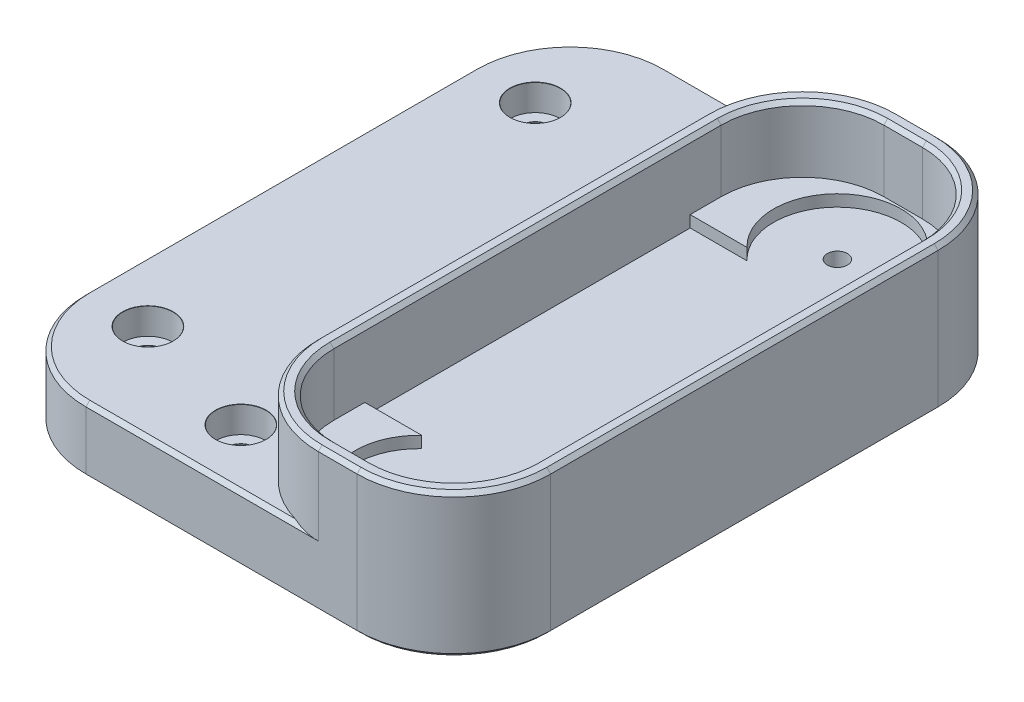
SolidWorks part; units mm, degrees
material "ABS"
ref_plane "Front Plane" through (0, 0, 0) normal (0, 0, 1) x (1, 0, 0)
ref_plane "Top Plane" through (0, 0, 0) normal (0, 1, 0) x (1, 0, 0)
ref_plane "Right Plane" through (0, 0, 0) normal (1, 0, 0) x (0, 0, -1)
sketch "Sketch1" plane through (0, 0, 0) normal (0, 0, 1) x (1, 0, 0)
  line L2 (0, 0) -> (60, 0)
  line L3 (60, 0) -> (60, 8.5)
  line L4 (60, 8.5) -> (30, 8.5)
  line L6 (30, 8.5) -> (0, 8.5)
  line L7 (0, 8.5) -> (0, 0)
  dimension "D1" = 30
  dimension "D5" = 30
  dimension "D6" = 8.5
extrude "Boss-Extrude1" add sketch "Sketch1" along normal blind 75
sketch "Sketch2" plane through (0, 8.5, 0) normal (0, 1, 0) x (1, 0, 0)
  line L1 (60, -75) -> (60, 0) construction
  circle A0 centre (45, -64.5) radius 1.3
  circle A1 centre (45, -10.5) radius 1.3
  point P12 (60, -37.5)
  dimension "D3" = 2.6
  dimension "D1" = 27
  dimension "D2" = 27
  dimension "D4" = 15
extrude "Cut-Extrude1" cut sketch "Sketch2" against normal blind 34
hole_wizard "CBORE for M3 Hex Socket Head Cap Screw1" positions "Sketch3" profile "Sketch4" counterbore size "M3" standard "ISO" end condition up to next
sketch "Sketch3" plane through (0, 8.5, 0) normal (0, 1, 0) x (1, 0, 0)
  line L2 (0, -75) -> (0, 0) construction
  point P0 (25, -67.5)
  point P2 (25, -7.5)
  point P14 (0, -37.5)
  point P15 (8, -12.5)
  point P17 (8, -62.5)
  dimension "D1" = 30
  dimension "D2" = 30
  dimension "D3" = 25
  dimension "D4" = 8
  dimension "D5" = 25
  dimension "D6" = 25
sketch "Sketch4" plane through (25, 8.5, 67.5) normal (1, 0, 0) x (0, 0, 1)
  line L0 (0, 0) -> (0, 8.5)
  line L1 (1.8, 8.475) -> (1.825, 8.5)
  line L2 (1.8, 8.475) -> (1.8, 3.425)
  line L3 (1.8, 3.425) -> (1.825, 3.4)
  line L4 (1.825, 3.4) -> (3.25, 3.4)
  line L5 (3.25, 3.4) -> (3.25, 0.025)
  line L6 (3.25, 0.025) -> (3.275, 0)
  line L7 (3.275, 0) -> (0, 0)
  line L8 (-3.25, 0.025) -> (-3.275, 0) construction
  line L9 (-1.8, 3.425) -> (-1.825, 3.4) construction
  line L11 (0, -6.35) -> (0, 107.95) construction
  line L12 (1.825, 8.5) -> (0, 8.5)
  line L13 (-1.8, 8.475) -> (-1.825, 8.5) construction
  dimension "Thru Hole Dia." = 3.6
  dimension "Thru Hole Depth" = 8.5
  dimension "C'Bore Dia." = 6.5
  dimension "C'Bore Depth" = 3.4
  dimension "Near C'Sink Dia." = 6.55
  dimension "Near C'Sink Angle" = 90
  dimension "Mid C'Sink Dia." = 3.65
  dimension "Mid C'Sink Angle" = 90
  dimension "Far C'Sink Dia." = 3.65
  dimension "Far C'Sink Angle" = 90
fillet "Fillet2" radius 12.5 4 edges at (60, 4.25, 0) (60, 4.25, 75) (0, 4.25, 0) (0, 4.25, 75)
sketch "Sketch5" plane through (0, 8.5, 0) normal (0, 1, 0) x (1, 0, 0)
  line L0 (60, -62.5) -> (60, -12.5) construction
  line L1 (47.5, 0) -> (42.5, 0)
  line L2 (60, -12.5) -> (60, -62.5)
  line L3 (47.5, -75) -> (42.5, -75)
  line L4 (30, -12.5) -> (30, -62.5)
  line L5 (60, 0) -> (30, -75) construction
  line L6 (60, -75) -> (30, 0) construction
  line L7 (47.5, 0) -> (12.5, 0) construction
  line L9 (47.5, -2) -> (42.5, -2)
  line L10 (58, -12.5) -> (58, -62.5)
  line L11 (47.5, -73) -> (42.5, -73)
  line L12 (32, -12.5) -> (32, -62.5)
  line L13 (58, -2) -> (32, -73) construction
  line L14 (58, -73) -> (32, -2) construction
  arc A0 (42.5, 0) -> (30, -12.5) centre (42.5, -12.5) ccw
  arc A1 (42.5, -75) -> (30, -62.5) centre (42.5, -62.5) cw
  arc A2 (60, -62.5) -> (47.5, -75) centre (47.5, -62.5) cw
  arc A3 (47.5, 0) -> (60, -12.5) centre (47.5, -12.5) cw
  arc A4 (42.5, -73) -> (32, -62.5) centre (42.5, -62.5) cw
  arc A5 (58, -62.5) -> (47.5, -73) centre (47.5, -62.5) cw
  arc A6 (42.5, -2) -> (32, -12.5) centre (42.5, -12.5) ccw
  arc A7 (47.5, -2) -> (58, -12.5) centre (47.5, -12.5) cw
  point P0 (45, -37.5)
  point P7 (60, -37.5)
  point P10 (45, -37.5)
  dimension "D5" = 12.5
  dimension "D6" = 10.5
  dimension "D1" = 15
  dimension "D2" = 30
  dimension "D3" = 2
  dimension "D4" = 2
extrude "Boss-Extrude2" add sketch "Sketch5" along normal blind 10
chamfer "Chamfer3" distance 0.5 angle 45 29 edges at (30, 0, 0) (3.6612, 0, 3.6612) (56.3388, 0, 3.6612) (0, 0, 37.5) (60, 0, 37.5) (3.6612, 0, 71.3388) (56.3388, 0, 71.3388) (30, 0, 75) (27.5, 8.5, 75) (3.6612, 8.5, 71.3388) (0, 8.5, 37.5) (3.6612, 8.5, 3.6612) (27.5, 8.5, 0) (56.3388, 18.5, 71.3388) (60, 18.5, 37.5) (45, 18.5, 75) (56.3388, 18.5, 3.6612) (33.6612, 18.5, 71.3388) (45, 18.5, 0) (30, 18.5, 37.5) (33.6612, 18.5, 3.6612) (54.9246, 18.5, 69.9246) (58, 18.5, 37.5) (45, 18.5, 73) (54.9246, 18.5, 5.0754) (35.0754, 18.5, 69.9246) (45, 18.5, 2) (32, 18.5, 37.5) (35.0754, 18.5, 5.0754)
sketch "Sketch6" plane through (0, 8.5, 0) normal (0, 1, 0) x (1, 0, 0)
  line L0 (58, -16.5) -> (32, -16.5)
  line L1 (58, -62.5) -> (58, -12.5) construction
  line L2 (32, -12.5) -> (32, -62.5) construction
  line L3 (58, -58.5) -> (32, -58.5)
  circle A0 centre (45, -10.5) radius 8.25
  circle A3 centre (45, -64.5) radius 8.25
  line M3 (32, -12.5) -> (32, -62.5)
  arc M4 (32, -62.5) -> (42.5, -73) centre (42.5, -62.5) ccw
  line M5 (42.5, -73) -> (47.5, -73)
  arc M6 (47.5, -73) -> (58, -62.5) centre (47.5, -62.5) ccw
  line M7 (58, -62.5) -> (58, -12.5)
  arc M8 (58, -12.5) -> (47.5, -2) centre (47.5, -12.5) ccw
  line M9 (47.5, -2) -> (42.5, -2)
  arc M10 (42.5, -2) -> (32, -12.5) centre (42.5, -12.5) ccw
  dimension "D1" = 16.5
  dimension "D2" = 16.5
  dimension "D3" = 6
  dimension "D4" = 6
extrude "Boss-Extrude3" add sketch "Sketch6" along normal blind 1.5 contours A0 L0 M7 M8 M9 M10 M3 | A3 L3 M3 M4 M5 M6 M7
equation "\"D2@Sketch2\"=\"D1@Sketch2\""
equation "\"D2@Sketch3\"=\"D1@Sketch3\""
equation "\"D6@Sketch3\"=\"D5@Sketch3\""
equation "\"D2@Sketch6\"=\"D1@Sketch6\""
